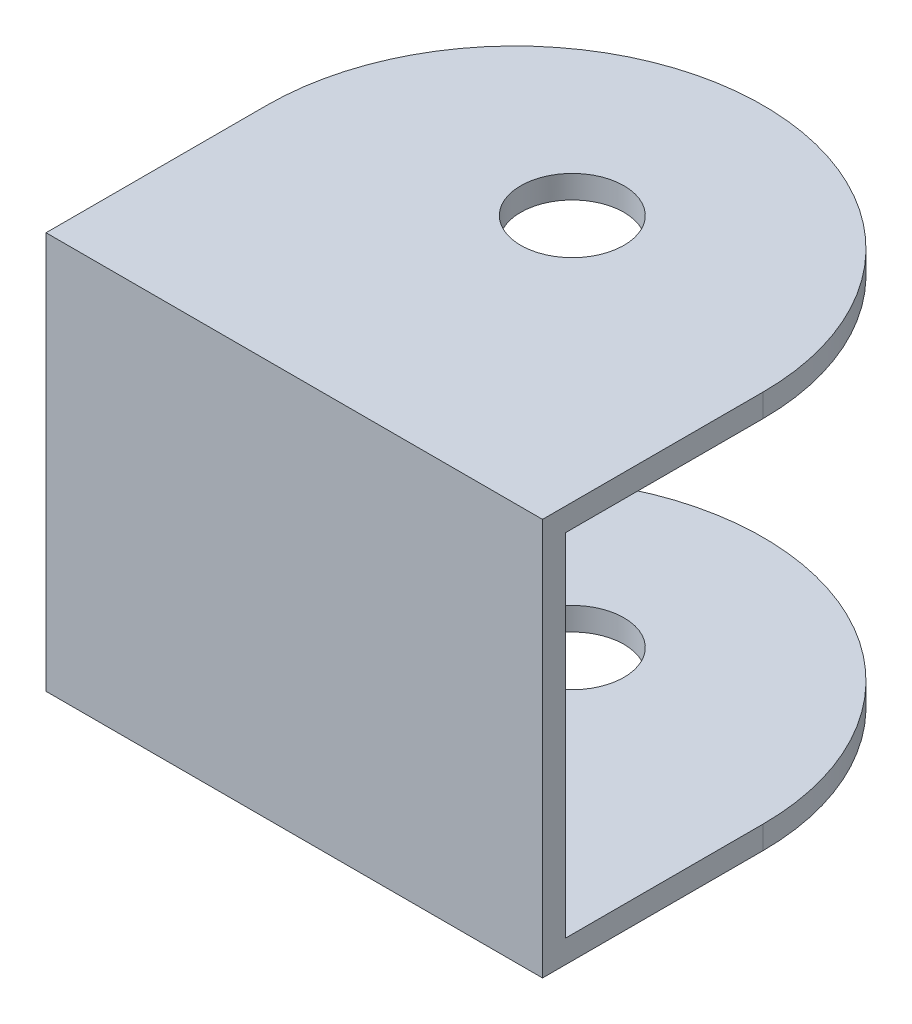
SolidWorks part; units mm, degrees
material "6061 Alloy"
ref_plane "Front Plane" through (0, 0, 0) normal (0, 0, 1) x (1, 0, 0)
ref_plane "Top Plane" through (0, 0, 0) normal (0, 1, 0) x (1, 0, 0)
ref_plane "Right Plane" through (0, 0, 0) normal (1, 0, 0) x (0, 0, -1)
sketch "Sketch1" plane through (0, 0, 0) normal (0, 1, 0) x (1, 0, 0)
  line L6 (15.875, 14.1111) -> (15.875, 0)
  line L7 (0, 0) -> (15.875, 0)
  line L8 (-15.875, 14.1111) -> (-15.875, 0)
  line L9 (-15.875, 0) -> (0, 0)
  arc A0 (-15.875, 14.1111) -> (15.875, 14.1111) centre (0, 14.1111) cw
  point P9 (0, 29.9861)
  dimension "D1" = 15.875
extrude "Boss-Extrude2" add sketch "Sketch1" along normal blind 25.4
ref_plane "Plane1" through (0, 12.7, 0) normal (0, 1, 0) x (1, 0, 0)
sketch "Sketch2" plane through (15.875, 0, 0) normal (1, 0, 0) x (0, 0, -1)
  line L0 (0, 25.4) -> (14.1111, 25.4) construction
  line L1 (1.4732, 1.4732) -> (66.1631, 1.4732)
  line L2 (1.4732, 1.4732) -> (1.4732, 23.9268)
  line L3 (1.4732, 23.9268) -> (66.1631, 23.9268)
  line L4 (66.1631, 1.4732) -> (66.1631, 23.9268)
  line L5 (0, 0) -> (14.1111, 0) construction
  line L6 (0, 25.4) -> (0, 0) construction
  dimension "D1" = 1.4732
  dimension "D2" = 1.4732
  dimension "D3" = 1.4732
extrude "Cut-Extrude1" cut sketch "Sketch2" against normal through all
sketch "Sketch5" plane through (0, 0, 0) normal (0, -1, 0) x (1, 0, 0)
  circle A0 centre (0, -17.78) radius 3.302
extrude "Cut-Extrude2" cut sketch "Sketch5" against normal through all contours A0
